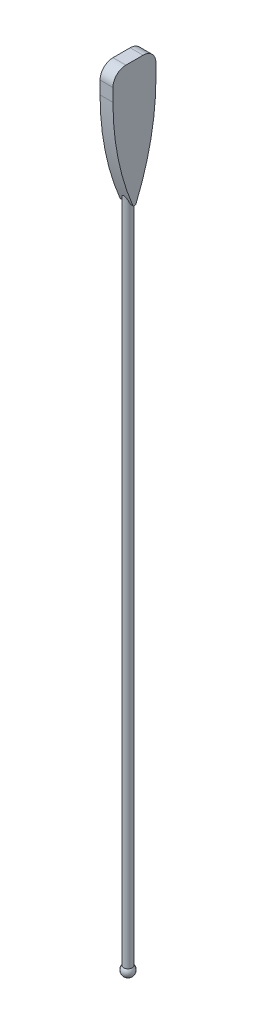
SolidWorks part; units mm, degrees
ref_plane "Front Plane" through (0, 0, 0) normal (0, 0, 1) x (1, 0, 0)
ref_plane "Top Plane" through (0, 0, 0) normal (0, 1, 0) x (1, 0, 0)
ref_plane "Right Plane" through (0, 0, 0) normal (1, 0, 0) x (0, 0, -1)
sketch "Sketch1" plane through (0, 0, 0) normal (0, 0, 1) x (1, 0, 0)
  line L0 (0, 0) -> (0, 46) construction
  line L2 (0.25, 0.2263) -> (0.25, 46)
  line L3 (0, -0.3372) -> (0, 0) construction
  line L4 (0, 46) -> (0.25, 46)
  line L5 (0, 46) -> (0, -0.3372)
  arc A1 (0, -0.3372) -> (0.25, 0.2263) centre (0, 0) ccw
  dimension "D1" = 46
  dimension "D2" = 0.5
revolve "Revolve1" add sketch "Sketch1" angle 360 about L5
sketch "Sketch3" plane through (0, 0, 0) normal (1, 0, 0) x (0, 0, -1)
  line L0 (0, 46) -> (0, 38.5052) construction
  line L1 (0.25, 46) -> (-0.25, 46) construction
  line L3 (1.25, 44.5) -> (-1.25, 44.5) construction
  line L4 (1.25, 44.5) -> (1.25, 45.25)
  line L5 (0.5, 46) -> (-0.5, 46)
  line L6 (-1.25, 44.5) -> (-1.25, 45.25)
  line L7 (1.25, 44.5) -> (-1.25, 46) construction
  line L8 (1.25, 46) -> (-1.25, 44.5) construction
  arc A0 (1.25, 45.25) -> (0.5, 46) centre (0.5, 45.25) ccw
  arc A1 (-0.5, 46) -> (-1.25, 45.25) centre (-0.5, 45.25) ccw
  arc A2 (-1.25, 44.5) -> (-0.0923, 38.7215) centre (13.75, 44.5) ccw
  arc A3 (1.25, 44.5) -> (0.0923, 38.7215) centre (-13.75, 44.5) cw
  arc A4 (0.0923, 38.7215) -> (-0.0923, 38.7215) centre (0, 38.76) cw
  point P5 (0, 45.25)
  dimension "D2" = 0.75
  dimension "D4" = 15
  dimension "D5" = 0.1
  dimension "D1" = 2.5
  dimension "D3" = 1.5
extrude "Boss-Extrude1" add sketch "Sketch3" along normal mid plane 0.75 contours A1 L6 A2 A4 A3 L4 A0 L5
